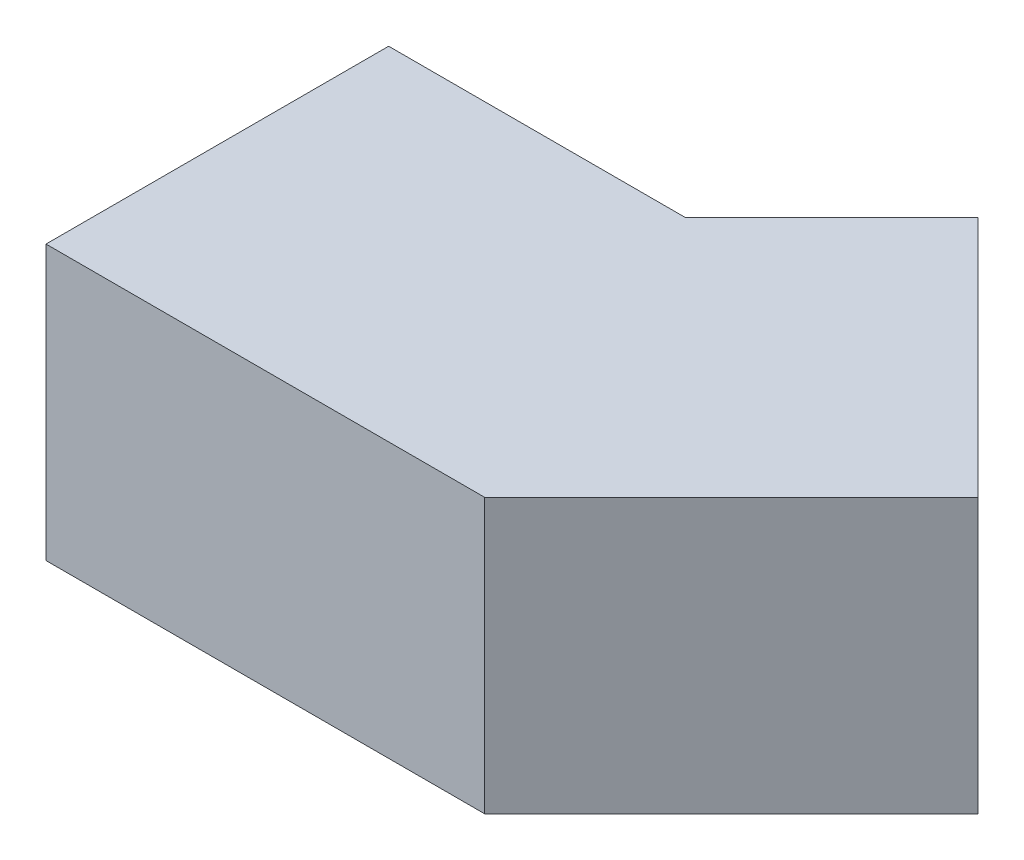
SolidWorks part; units mm, degrees
ref_plane "Front Plane" through (0, 0, 0) normal (0, 0, 1) x (1, 0, 0)
ref_plane "Top Plane" through (0, 0, 0) normal (0, 1, 0) x (1, 0, 0)
ref_plane "Right Plane" through (0, 0, 0) normal (1, 0, 0) x (0, 0, -1)
sketch "Sketch1" plane through (0, 0, 0) normal (0, 1, 0) x (1, 0, 0)
  line L0 (0, 0) -> (32, 0)
  line L1 (32, 0) -> (50, 18)
  line L2 (50, 18) -> (32.3223, 35.6777)
  line L3 (32.3223, 35.6777) -> (21.6447, 25)
  line L4 (21.6447, 25) -> (0, 25)
  line L5 (0, 25) -> (0, 0)
  dimension "D1" = 25
  dimension "D4" = 50
  dimension "D5" = 135
  dimension "D6" = 32
  dimension "D7" = 25
extrude "Boss-Extrude1" add sketch "Sketch1" along normal blind 20
